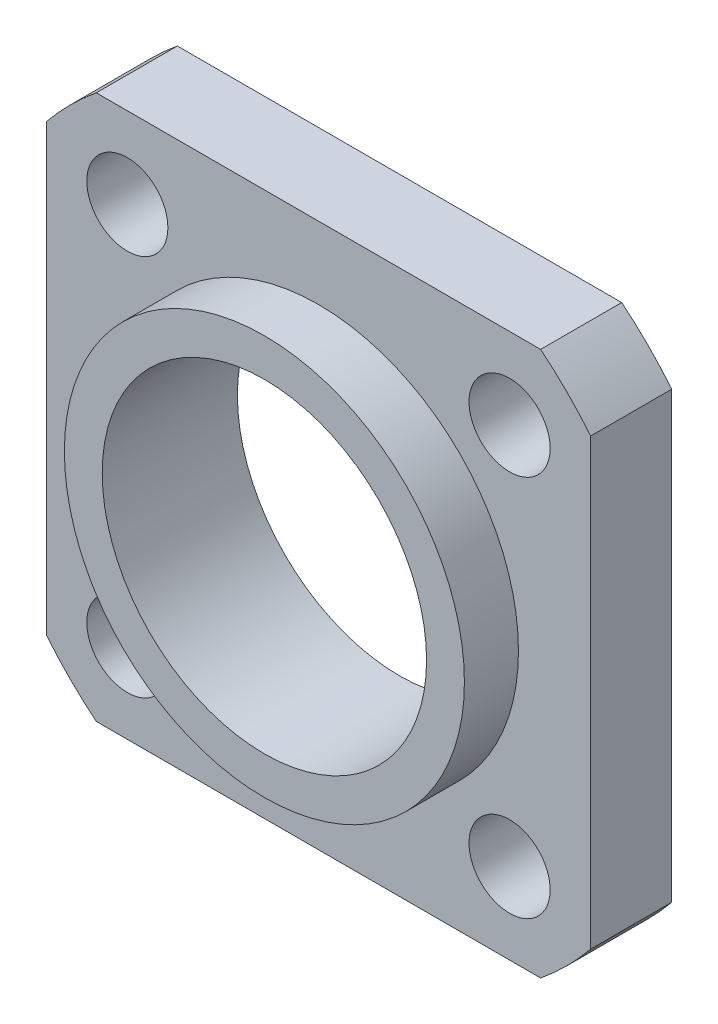
SolidWorks part; units mm, degrees
ref_plane "前视基准面" through (0, 0, 0) normal (0, 0, 1) x (1, 0, 0)
ref_plane "上视基准面" through (0, 0, 0) normal (0, 1, 0) x (1, 0, 0)
ref_plane "右视基准面" through (0, 0, 0) normal (1, 0, 0) x (0, 0, -1)
other "Configuration Table"
sketch "草图1" plane through (0, 0, 0) normal (0, 0, 1) x (1, 0, 0)
  line L0 (-7.0711, 7.0711) -> (0, 0) construction
  line L1 (0, 0) -> (-10, 0) construction
  circle A0 centre (0, 0) radius 10 construction
  circle A1 centre (0, 0) radius 13
  circle A2 centre (0, 0) radius 6
  circle A3 centre (-7.0711, 7.0711) radius 1.5
  circle A4 centre (7.0711, 7.0711) radius 1.5
  circle A5 centre (7.0711, -7.0711) radius 1.5
  circle A6 centre (-7.0711, -7.0711) radius 1.5
  point P17 (0, 0)
  dimension "D1" = 20
  dimension "D2" = 26
  dimension "D3" = 12
  dimension "D5" = 3
  dimension "D4" = 45
  dimension "D6" = 4
extrude "凸台-拉伸1" add sketch "草图1" along normal blind 3
sketch "草图2" plane through (0, 0, 3) normal (0, 0, 1) x (1, 0, 0)
  circle A0 centre (0, 0) radius 7.4
  circle A1 centre (0, 0) radius 6
  dimension "D1" = 14.8
  dimension "D2" = 12
extrude "凸台-拉伸2" add sketch "草图2" along normal blind 2
sketch "草图3" plane through (0, 0, 3) normal (0, 0, 1) x (1, 0, 0)
  line L0 (-8.2203, 10.0711) -> (8.2203, 10.0711)
  line L1 (10.0711, 8.2203) -> (10.0711, -8.2203)
  line L2 (8.2203, -10.0711) -> (-8.2203, -10.0711)
  line L3 (-10.0711, -8.2203) -> (-10.0711, 8.2203)
  circle A0 centre (0, 0) radius 13 construction
  circle A1 centre (-7.0711, 7.0711) radius 1.5 construction
  arc A2 (-10.0711, 8.2203) -> (-10.0711, -8.2203) centre (0, 0) ccw
  arc A3 (8.2203, 10.0711) -> (-8.2203, 10.0711) centre (0, 0) ccw
  arc A4 (10.0711, -8.2203) -> (10.0711, 8.2203) centre (0, 0) ccw
  arc A5 (-8.2203, -10.0711) -> (8.2203, -10.0711) centre (0, 0) ccw
  point P16 (0, 0)
  dimension "D1" = 3
  dimension "D2" = 4
extrude "切除-拉伸1" cut sketch "草图3" against normal blind 41
